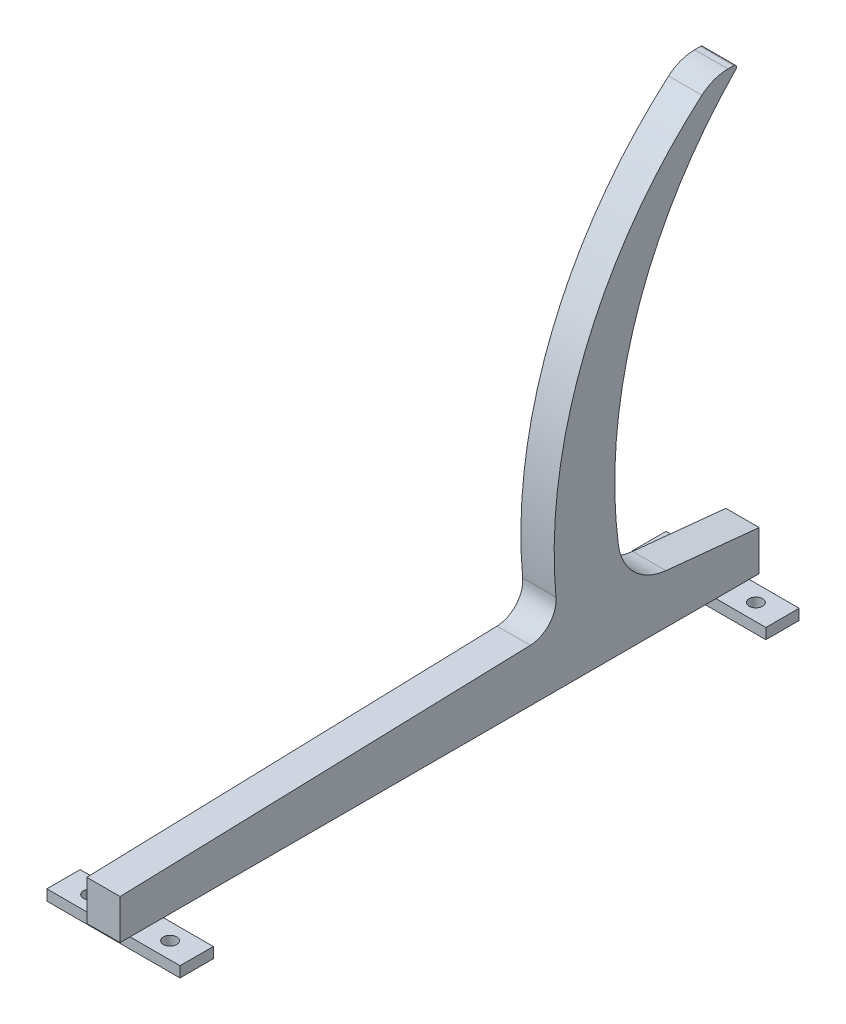
SolidWorks part; units mm, degrees
ref_plane "Front Plane" through (0, 0, 0) normal (0, 0, 1) x (1, 0, 0)
ref_plane "Top Plane" through (0, 0, 0) normal (0, 1, 0) x (1, 0, 0)
ref_plane "Right Plane" through (0, 0, 0) normal (1, 0, 0) x (0, 0, -1)
sketch "Sketch1" plane through (0, 0, 0) normal (1, 0, 0) x (0, 0, -1)
  line L0 (-304.8, 0) -> (304.8, 0)
  line L1 (-304.8, 38.1) -> (86.4011, 49.9546)
  line L2 (304.8, 38.1) -> (177.8, 50.8)
  line L3 (-304.8, 38.1) -> (-304.8, 0)
  line L4 (304.8, 38.1) -> (304.8, 0)
  line L5 (261.2429, 431.8) -> (286.6429, 431.8)
  arc A0 (110.9251, 77.6672) -> (261.2429, 431.8) centre (515.62, 114.8564) cw
  arc A1 (177.8, 50.8) -> (286.6429, 431.8) centre (573.4087, 143.8307) cw
  arc A2 (86.4011, 49.9546) -> (110.9251, 77.6672) centre (85.6317, 75.3429) ccw
  point P3 (0, 0)
  point P14 (114.3, 50.8)
  dimension "D4" = 406.4
  dimension "D5" = 406.4
  dimension "D13" = 25.4
  dimension "D1" = 609.6
  dimension "D2" = 50.8
  dimension "D3" = 50.8
  dimension "D6" = 515.62
  dimension "D7" = 381
  dimension "D8" = 63.5
  dimension "D9" = 38.1
  dimension "D10" = 38.1
  dimension "D11" = 127
  dimension "D12" = 25.4
extrude "Boss-Extrude1" add sketch "Sketch1" along normal mid plane 31.75
fillet "Fillet1" radius 38.1 1 edges at (0, 431.8, -261.2429)
fillet "Fillet2" radius 50.8 1 edges at (0, 50.8, -177.8)
sketch "Sketch2" plane through (0, 0, 0) normal (0, -1, 0) x (1, 0, 0)
  line L0 (0, 0) -> (0, 304.8) construction
  line L1 (15.875, 304.8) -> (-15.875, 304.8) construction
  line L2 (0, 0) -> (-69.9872, 0) construction
  line L3 (-63.5, 295.275) -> (63.5, 295.275)
  line L4 (-63.5, 295.275) -> (-63.5, 263.525)
  line L5 (-63.5, 263.525) -> (63.5, 263.525)
  line L6 (63.5, 295.275) -> (63.5, 263.525)
  line L7 (-63.5, 295.275) -> (63.5, 263.525) construction
  line L8 (-63.5, 263.525) -> (63.5, 295.275) construction
  line L9 (-63.5, -263.525) -> (63.5, -263.525)
  line L10 (63.5, -295.275) -> (63.5, -263.525)
  line L11 (-63.5, -295.275) -> (63.5, -295.275)
  line L12 (-63.5, -295.275) -> (-63.5, -263.525)
  circle A0 centre (-38.1, 279.4) radius 6.35
  circle A1 centre (38.1, 279.4) radius 6.35
  circle A2 centre (38.1, -279.4) radius 6.35
  circle A3 centre (-38.1, -279.4) radius 6.35
  point P5 (0, 279.4)
  dimension "D4" = 12.7
  dimension "D5" = 12.7
  dimension "D1" = 279.4
  dimension "D2" = 31.75
  dimension "D3" = 127
  dimension "D6" = 76.2
  dimension "D7" = 38.1
extrude "Boss-Extrude2" add sketch "Sketch2" along normal blind 10.16
fillet "Fillet3" radius 2.54 1 edges at (0, 431.8, -286.6429)
